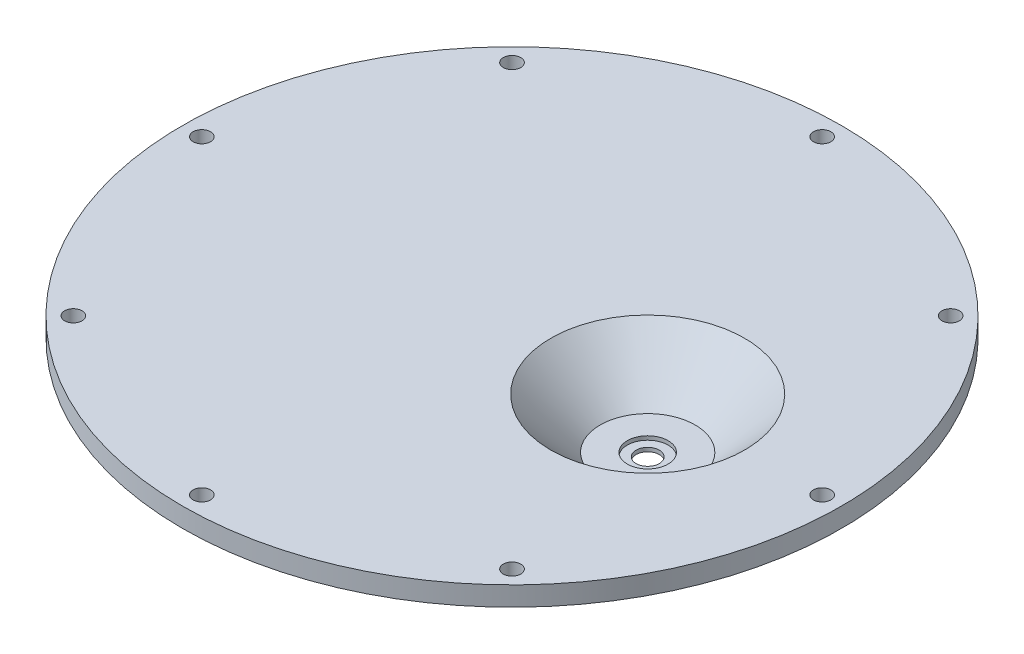
SolidWorks part; units mm, degrees
material "1060 合金"
ref_plane "前视基准面" through (0, 0, 0) normal (0, 0, 1) x (1, 0, 0)
ref_plane "上视基准面" through (0, 0, 0) normal (0, 1, 0) x (1, 0, 0)
ref_plane "右视基准面" through (0, 0, 0) normal (1, 0, 0) x (0, 0, -1)
sketch "草图2" plane through (0, 0, 0) normal (0, 0, 1) x (1, 0, 0)
  line L8 (35, 1.7137) -> (35, -14.0607) construction
  line L9 (-2.0392, 0) -> (43.8989, 0) construction
  line L22 (32, -15) -> (32, -14)
  line L23 (32, -14) -> (29.75, -14)
  line L24 (29.75, -14) -> (29.75, -13)
  line L25 (29.75, -13) -> (22.75, -13)
  line L32 (32, -15) -> (23, -15)
  line L37 (10, 0) -> (10, -5)
  line L38 (10, -5) -> (23, -15)
  line L39 (10, 0) -> (22.75, -13)
  dimension "D1" = 35
  dimension "D2" = 3
  dimension "D3" = 5.25
  dimension "D4" = 5
  dimension "D5" = 1
  dimension "D6" = 1
  dimension "D7" = 25
  dimension "D9" = 9
  dimension "D10" = 7
  dimension "D12" = 13
revolve "物镜观察窗" add sketch "草图2" angle 360 about L8
sketch "草图6" plane through (0, 0, 0) normal (0, 1, 0) x (1, 0, 0)
  circle A0 centre (0, 0) radius 85
  circle A1 centre (35, 0) radius 25 construction
  circle A2 centre (35, 0) radius 25
  dimension "D1" = 170
extrude "换样上盖" add sketch "草图6" against normal blind 5
hole_wizard "M4*8 固定孔" positions "草图8" profile "草图9" hole size "Ø5.0" standard "ISO" end condition through all
sketch "草图8" plane through (0, 0, 0) normal (0, 1, 0) x (1, 0, 0)
  point P0 (80, 0)
  point P12 (-80, 0)
  point P13 (-56.5685, 56.5685)
  point P14 (0, 80)
  point P18 (56.5685, -56.5685)
  point P20 (0, -80)
  point P22 (-56.5685, -56.5685)
  point P24 (56.5685, 56.5685)
  point P33 (56.5685, -56.5685)
  point P34 (0, -80)
  point P35 (-56.5685, -56.5685)
  point P36 (-80, 0)
  point P37 (-56.5685, 56.5685)
  point P38 (0, 80)
  point P39 (56.5685, 56.5685)
  dimension "D1" = 80
  dimension "D2" = 8
  dimension "D3" = 8
sketch "草图9" plane through (80, 0, 0) normal (1, 0, 0) x (0, 0, 1)
  line L0 (0, 0) -> (0, 15)
  line L1 (0, 15) -> (2.25, 15)
  line L2 (2.25, 15) -> (2.25, 0)
  line L5 (2.25, 0) -> (0, 0)
  line L11 (0, -6.35) -> (0, 107.95) construction
  dimension "通孔孔直径" = 4.5
  dimension "通孔孔深度" = 15
